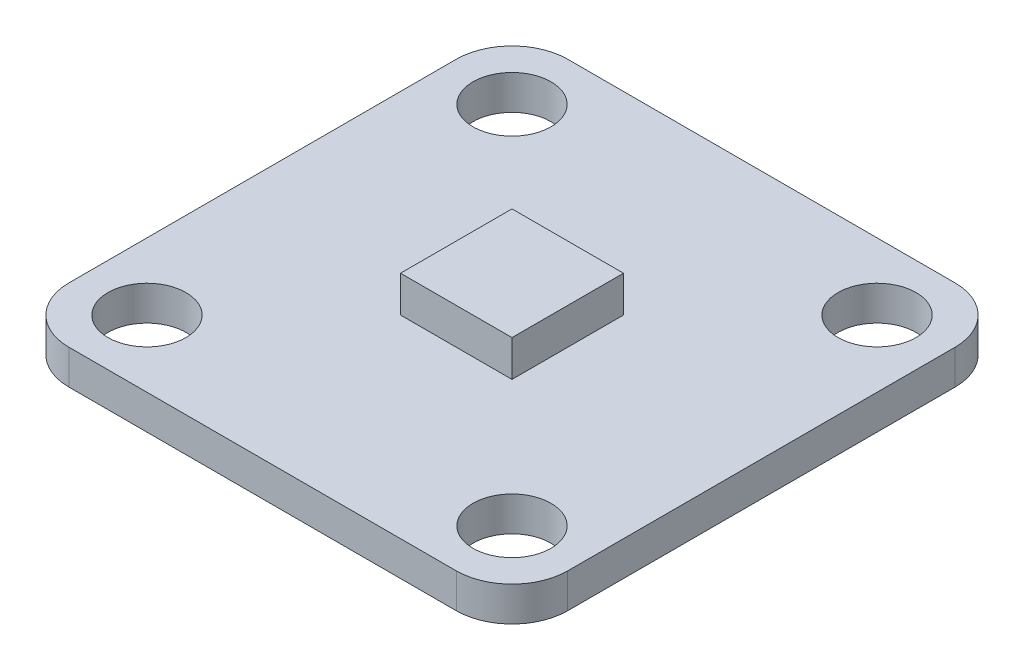
SolidWorks part; units mm, degrees
ref_plane "Front Plane" through (0, 0, 0) normal (0, 0, 1) x (1, 0, 0)
ref_plane "Top Plane" through (0, 0, 0) normal (0, 1, 0) x (1, 0, 0)
ref_plane "Right Plane" through (0, 0, 0) normal (1, 0, 0) x (0, 0, -1)
sketch "Sketch1" plane through (0, 26.884, 0) normal (0, -1, 0) x (1, 0, 0)
  line L1 (0.0635, 11.3665) -> (22.7965, 11.3665)
  line L2 (0.0635, 11.3665) -> (0.0635, -11.3665)
  line L3 (0.0635, -11.3665) -> (22.7965, -11.3665)
  line L4 (22.7965, 11.3665) -> (22.7965, -11.3665)
  circle A3 centre (11.43, 0) radius 10.6567 construction
  circle A4 centre (11.43, 0) radius 6.5405 construction
  point P4 (22.7965, 0)
  point P7 (11.43, 0)
  point P10 (11.43, -11.3665)
  dimension "D1" = 22.733
extrude "Boss-Extrude1" add sketch "Sketch1" along normal blind 1.5748 contours L3 L4 L1 L2
fillet "Fillet1" radius 2.54 4 edges at (22.7965, 26.0966, 11.3665) (0.0635, 26.0966, 11.3665) (22.7965, 26.0966, -11.3665) (0.0635, 26.0966, -11.3665)
sketch "Sketch2" plane through (0, 26.884, 0) normal (0, 1, 0) x (1, 0, 0)
  line L0 (11.43, 11.3665) -> (11.43, -11.3665) construction
  line L1 (2.6035, 11.3665) -> (20.2565, 11.3665) construction
  line L2 (2.6035, -11.3665) -> (20.2565, -11.3665) construction
  line L3 (22.7965, 0) -> (0, 0) construction
  line L4 (22.7965, -8.8265) -> (22.7965, 8.8265) construction
  circle A0 centre (19.7485, 8.3185) radius 1.778
  circle A2 centre (3.1115, 8.3185) radius 1.778
  circle A3 centre (19.7485, -8.3185) radius 1.778
  circle A4 centre (3.1115, -8.3185) radius 1.778
  dimension "D1" = 3.556
  dimension "D2" = 3.048
  dimension "D3" = 3.048
extrude "Cut-Extrude1" cut sketch "Sketch2" against normal blind 1.5748
sketch "Sketch3" plane through (0, 26.884, 0) normal (0, 1, 0) x (1, 0, 0)
  line L0 (2.6035, 11.3665) -> (20.2565, 11.3665) construction
  line L1 (8.89, -2.54) -> (13.97, -2.54)
  line L2 (8.89, -2.54) -> (8.89, 2.54)
  line L3 (8.89, 2.54) -> (13.97, 2.54)
  line L4 (13.97, -2.54) -> (13.97, 2.54)
  line L5 (8.89, -2.54) -> (13.97, 2.54) construction
  line L6 (8.89, 2.54) -> (13.97, -2.54) construction
  line L7 (22.7965, -8.8265) -> (22.7965, 8.8265) construction
  point P0 (11.43, 0)
  point P7 (11.43, 11.3665)
  point P10 (22.7965, 0)
  dimension "D1" = 5.08
  dimension "D2" = 5.08
extrude "Boss-Extrude2" add sketch "Sketch3" along normal blind 1.651
equation "\".1i\"=1.905"
